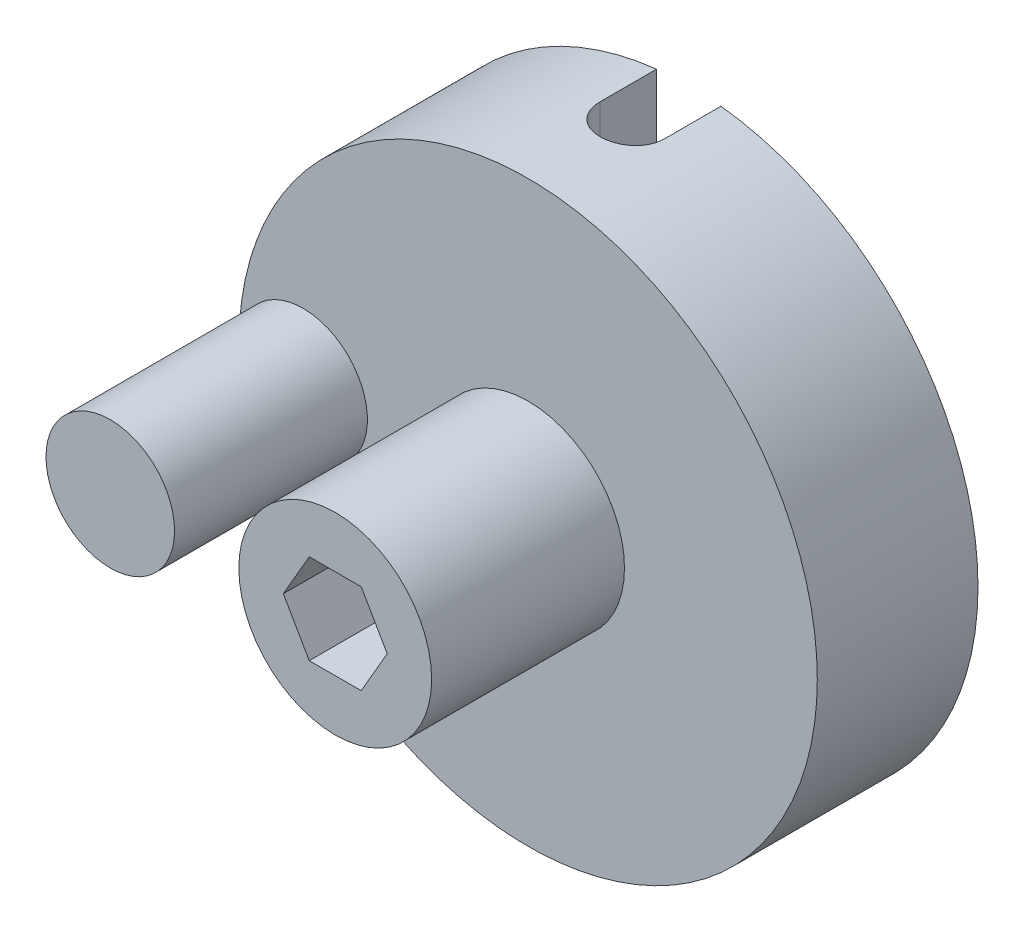
SolidWorks part; units mm, degrees
ref_plane "Front Plane" through (0, 0, 0) normal (0, 0, 1) x (1, 0, 0)
ref_plane "Top Plane" through (0, 0, 0) normal (0, 1, 0) x (1, 0, 0)
ref_plane "Right Plane" through (0, 0, 0) normal (1, 0, 0) x (0, 0, -1)
sketch "Sketch1" plane through (0, 0, 0) normal (0, 0, 1) x (1, 0, 0)
  circle A0 centre (0, 0) radius 9
  dimension "D1" = 18
extrude "Boss-Extrude1" add sketch "Sketch1" along normal blind 5
sketch "Sketch2" plane through (0, 0, 5) normal (0, 0, 1) x (1, 0, 0)
  circle A0 centre (0, 0) radius 3
  circle A1 centre (-7, 0) radius 2
  dimension "D1" = 7
extrude "Boss-Extrude2" add sketch "Sketch2" along normal blind 6
sketch "Sketch3" plane through (0, 0, 11) normal (0, 0, 1) x (1, 0, 0)
  line L0 (0, 0) -> (-6.7973, 0) construction
  line L2 (-1.6166, 0) -> (-0.8083, -1.4)
  line L3 (-0.8083, -1.4) -> (0.8083, -1.4)
  line L4 (0.8083, -1.4) -> (1.6166, 0)
  line L5 (1.6166, 0) -> (0.8083, 1.4)
  line L6 (0.8083, 1.4) -> (-0.8083, 1.4)
  line L7 (-0.8083, 1.4) -> (-1.6166, 0)
  circle A0 centre (0, 0) radius 1.4 construction
  dimension "D1" = 2.8
extrude "Cut-Extrude1" cut sketch "Sketch3" against normal through all
sketch "Sketch4" plane through (0, 0, 0) normal (0, 0, -1) x (-1, 0, 0)
  line L1 (-4.0992, 0) -> (-2.0496, -3.55)
  line L2 (-2.0496, -3.55) -> (2.0496, -3.55)
  line L3 (2.0496, -3.55) -> (4.0992, 0)
  line L4 (4.0992, 0) -> (2.0496, 3.55)
  line L5 (2.0496, 3.55) -> (-2.0496, 3.55)
  line L6 (-2.0496, 3.55) -> (-4.0992, 0)
  circle A0 centre (0, 0) radius 3.55 construction
  dimension "D1" = 7.1
extrude "Cut-Extrude2" cut sketch "Sketch4" against normal blind 3
sketch "Sketch5" plane through (0, 3.55, 0) normal (0, -1, 0) x (1, 0, 0)
  line L0 (0, -4.8816) -> (0, 1.7562) construction
  line L1 (0, 2.7562) -> (0, 10.8942) construction
  line L3 (1, 1.7562) -> (1, -1.0404)
  line L4 (1, -1.0404) -> (-1, -1.0404)
  line L5 (-1, 1.7562) -> (-1, -1.0404)
  arc A0 (1, 1.7562) -> (-1, 1.7562) centre (0, 1.7562) ccw
  dimension "D1" = 2
extrude "Cut-Extrude3" cut sketch "Sketch5" against normal blind 8
